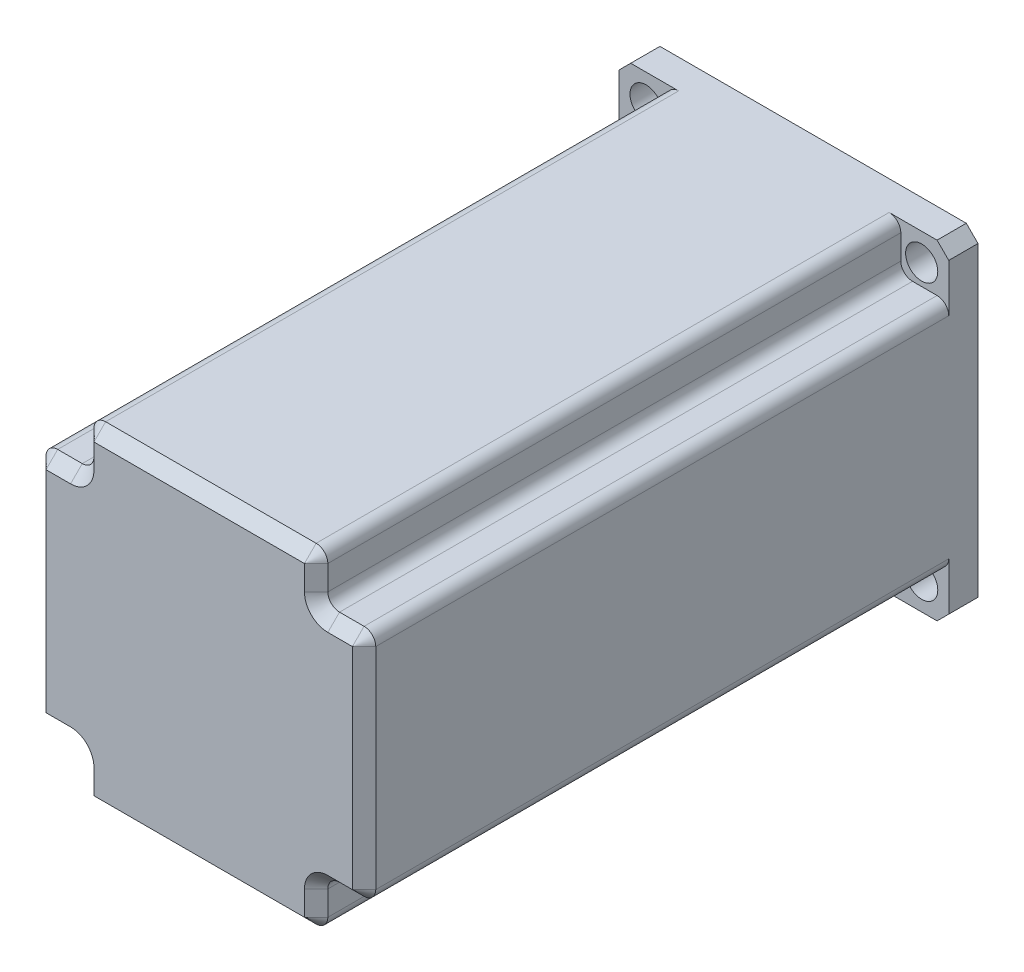
SolidWorks part; units mm, degrees
material "AISI 304"
ref_plane "Płaszczyzna przednia" through (0, 0, 0) normal (0, 0, 1) x (1, 0, 0)
ref_plane "Płaszczyzna górna" through (0, 0, 0) normal (0, 1, 0) x (1, 0, 0)
ref_plane "Płaszczyzna prawa" through (0, 0, 0) normal (1, 0, 0) x (0, 0, -1)
sketch "Szkic1" plane through (0, 0, 0) normal (0, 0, 1) x (1, 0, 0)
  line L1 (-28.2, 28.2) -> (28.2, 28.2)
  line L2 (-28.2, 28.2) -> (-28.2, -28.2)
  line L3 (-28.2, -28.2) -> (28.2, -28.2)
  line L4 (28.2, 28.2) -> (28.2, -28.2)
  line L5 (-28.2, 28.2) -> (28.2, -28.2) construction
  line L6 (-28.2, -28.2) -> (28.2, 28.2) construction
  point P0 (0, 0)
  dimension "D1" = 56.4
extrude "Dodanie-wyciągnięcie1" add sketch "Szkic1" along normal blind 105
sketch "Szkic2" plane through (0, 0, 0) normal (0, 0, -1) x (-1, 0, 0)
  circle A0 centre (0, 0) radius 4
  dimension "D1" = 8
extrude "Dodanie-wyciągnięcie2" add sketch "Szkic2" along normal blind 20
sketch "Szkic3" plane through (0, 0, 105) normal (0, 0, 1) x (1, 0, 0)
  line L0 (0, 0) -> (0, 50000) construction
  line L1 (-28.2, 28.2) -> (-20, 28.2)
  line L2 (-28.2, 28.2) -> (-28.2, 20)
  line L3 (-28.2, 20) -> (-20, 20)
  line L4 (-20, 28.2) -> (-20, 20)
  line L5 (0, 0) -> (50000, 0) construction
  line L6 (20, 28.2) -> (20, 20)
  line L7 (28.2, 20) -> (20, 20)
  line L8 (28.2, 28.2) -> (28.2, 20)
  line L9 (28.2, 28.2) -> (20, 28.2)
  line L10 (28.2, -28.2) -> (20, -28.2)
  line L11 (28.2, -28.2) -> (28.2, -20)
  line L12 (28.2, -20) -> (20, -20)
  line L13 (20, -28.2) -> (20, -20)
  line L14 (-20, -28.2) -> (-20, -20)
  line L15 (-28.2, -20) -> (-20, -20)
  line L16 (-28.2, -28.2) -> (-28.2, -20)
  line L17 (-28.2, -28.2) -> (-20, -28.2)
  dimension "D1" = 40
  dimension "D2" = 40
extrude "Wytnij-wyciągnięcie1" cut sketch "Szkic3" against normal offset from surface (100 mm away) 5 up to face at (4, 0, 0)
fillet "Zaokrąglenie1" radius 2 12 edges at (-20, -28.2, 55) (-20, -20, 55) (-28.2, -20, 55) (20, -28.2, 55) (20, -20, 55) (28.2, -20, 55) (28.2, 20, 55) (20, 20, 55) (20, 28.2, 55) (-20, 28.2, 55) (-20, 20, 55) (-28.2, 20, 55)
chamfer "Sfazowanie1" distance 2 angle 45 28 edges at (-28.2, 0, 105) (-27.6142, -19.4142, 105) (-27.6142, 19.4142, 105) (-24.1, -20, 105) (-24.1, 20, 105) (-20.5858, -20.5858, 105) (-20.5858, 20.5858, 105) (-20, -24.1, 105) (-20, 24.1, 105) (-19.4142, -27.6142, 105) (-19.4142, 27.6142, 105) (0, -28.2, 105) (0, 28.2, 105) (19.4142, -27.6142, 105) (19.4142, 27.6142, 105) (20, -24.1, 105) (20, 24.1, 105) (20.5858, -20.5858, 105) (20.5858, 20.5858, 105) (24.1, -20, 105) (24.1, 20, 105) (27.6142, -19.4142, 105) (27.6142, 19.4142, 105) (28.2, 0, 105) (28.2, -28.2, 2.5) (28.2, 28.2, 2.5) (-28.2, -28.2, 2.5) (-28.2, 28.2, 2.5)
hole_wizard "Otwór pod śrubę M51" positions "Szkic4" profile "Szkic5" hole size "M5" standard "ISO"
sketch "Szkic4" plane through (0, 0, 0) normal (0, 0, -1) x (-1, 0, 0)
  line L0 (0, 0) -> (0, 50000) construction
  line L1 (0, 0) -> (50000, 0) construction
  point P0 (-23.57, 23.57)
  point P11 (0, 0)
  point P12 (23.57, 23.57)
  point P13 (23.57, -23.57)
  point P14 (-23.57, -23.57)
  dimension "D1" = 47.14
  dimension "D2" = 47.14
sketch "Szkic5" plane through (23.57, 23.57, 0) normal (1, 0, 0) x (0, 1, 0)
  line L0 (0, 0) -> (0, 12.6524)
  line L1 (0, 12.6524) -> (2.75, 11)
  line L2 (2.75, 11) -> (2.75, 0)
  line L5 (2.75, 0) -> (0, 0)
  line L10 (0, 12.6524) -> (-2.75, 11) construction
  line L11 (0, -6.35) -> (0, 107.95) construction
  dimension "Średnica otworu" = 5.5
  dimension "Głębokość otworu" = 11
  dimension "Kąt wiertła" = 118
chamfer "Sfazowanie2" distance 1 angle 45 1 edges at (-4, 0, -20)
